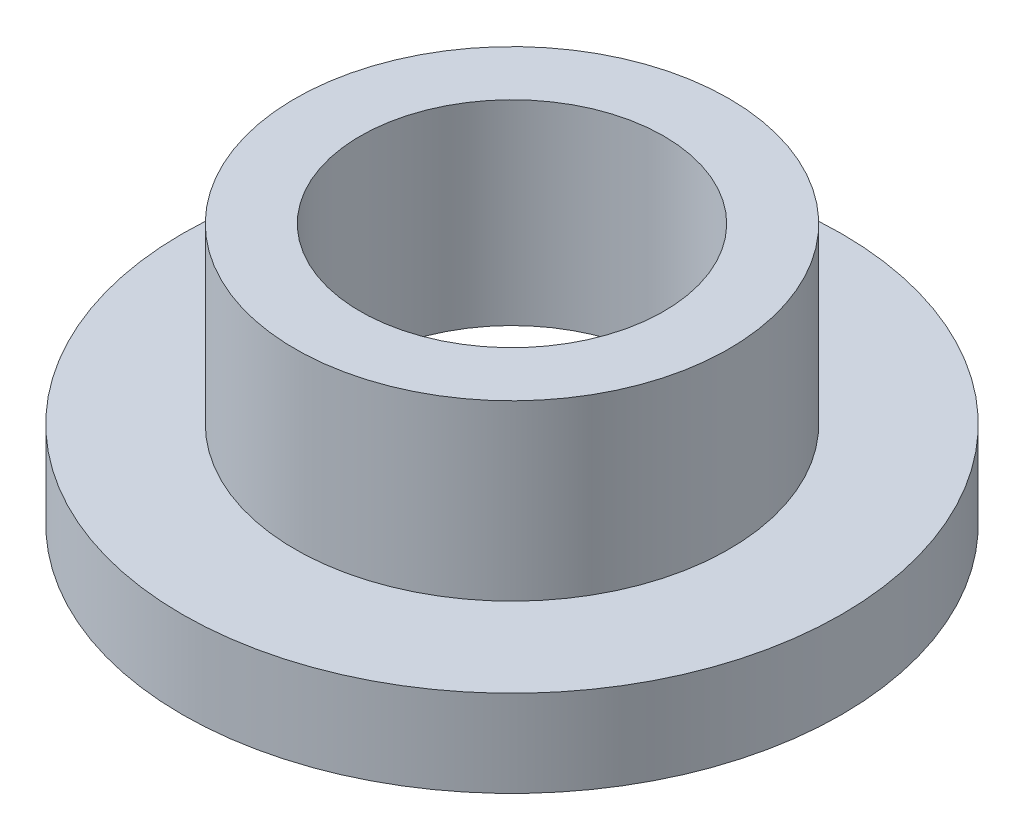
SolidWorks part; units mm, degrees
material "6061-T6 (SS)"
ref_plane "Front Plane" through (0, 0, 0) normal (0, 0, 1) x (1, 0, 0)
ref_plane "Top Plane" through (0, 0, 0) normal (0, 1, 0) x (1, 0, 0)
ref_plane "Right Plane" through (0, 0, 0) normal (1, 0, 0) x (0, 0, -1)
sketch "Sketch1" plane through (0, 0, 0) normal (0, 0, 1) x (1, 0, 0)
  line L0 (0, 0) -> (0, 45) construction
  line L5 (17.5, 7.4614) -> (38, 0)
  line L7 (38, 0) -> (38, 30)
  line L10 (0, 0) -> (38, 0) construction
  line L13 (17.5, 30) -> (38, 30)
  line L14 (0, 45) -> (0, 43)
  line L18 (17.5, 7.4614) -> (17.5, 30)
  line L19 (25, 30) -> (25, 10)
  line L20 (25, 10) -> (38, 10)
  dimension "D1" = 76
  dimension "D2" = 20
  dimension "D3" = 35
  dimension "D4" = 10
  dimension "D5" = 30
  dimension "D6" = 45
  dimension "D7" = 50
revolve "Revolve1" add sketch "Sketch1" angle 360 about L0
